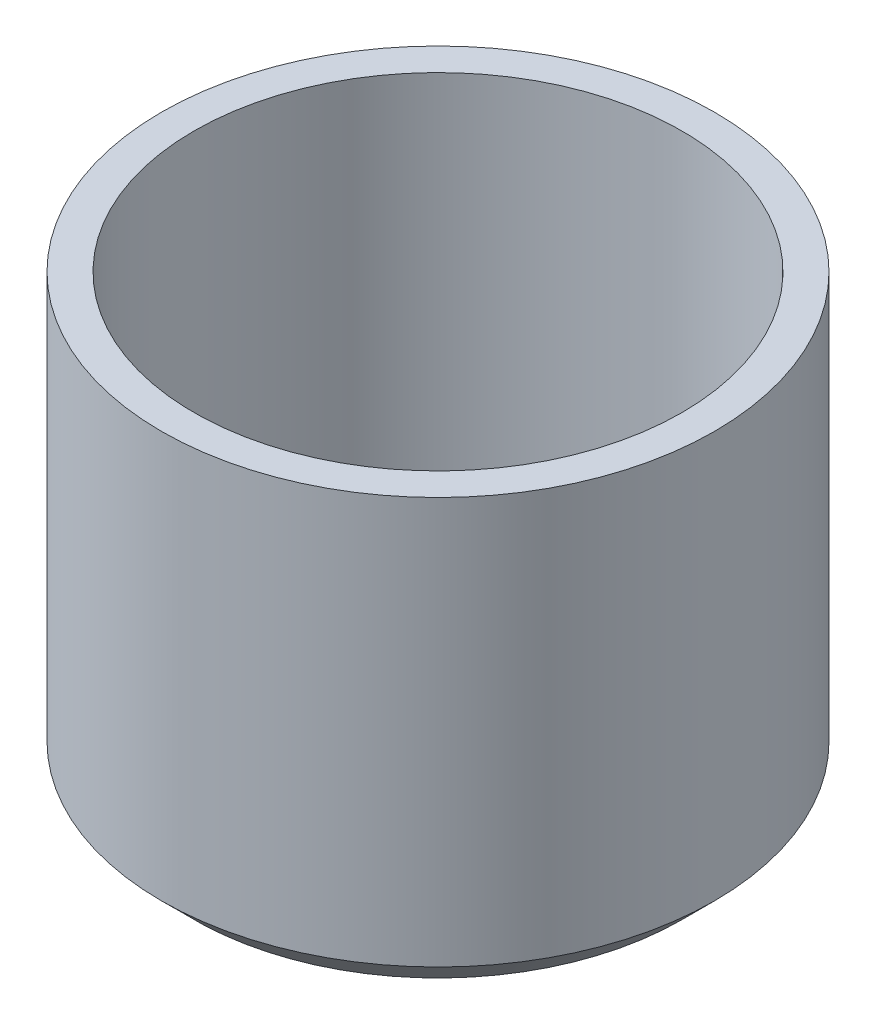
SolidWorks part; units mm, degrees
ref_plane "Front Plane" through (0, 0, 0) normal (0, 0, 1) x (1, 0, 0)
ref_plane "Top Plane" through (0, 0, 0) normal (0, 1, 0) x (1, 0, 0)
ref_plane "Right Plane" through (0, 0, 0) normal (1, 0, 0) x (0, 0, -1)
sketch "Sketch1" plane through (0, 0, 0) normal (0, 0, 1) x (1, 0, 0)
  line L0 (0, -368.0402) -> (0, 18033.9676) construction
  line L1 (0, 0) -> (-9, 0)
  line L2 (-10.2, 1.2) -> (-10.2, 16.2)
  line L3 (-10.2, 16.2) -> (-9, 16.2)
  line L4 (-9, 16.2) -> (-9, 1.6971)
  line L5 (-9, 1.6971) -> (-8.5029, 1.2)
  line L6 (-8.5029, 1.2) -> (0, 1.2)
  line L7 (0, 1.2) -> (0, 0)
  line L8 (-10.2, 1.2) -> (-9, 0)
  line L9 (-10.2, 0) -> (-10.2, 1.2) construction
  line L10 (-9, 0) -> (-10.2, 0) construction
  point P12 (0, 0)
  point P13 (0, 0)
  dimension "D1" = 1.2
  dimension "D2" = 1.2
  dimension "D3" = 18
  dimension "D4" = 1.2
  dimension "D5" = 15
revolve "Revolve1" add sketch "Sketch1" angle 360 about L0
